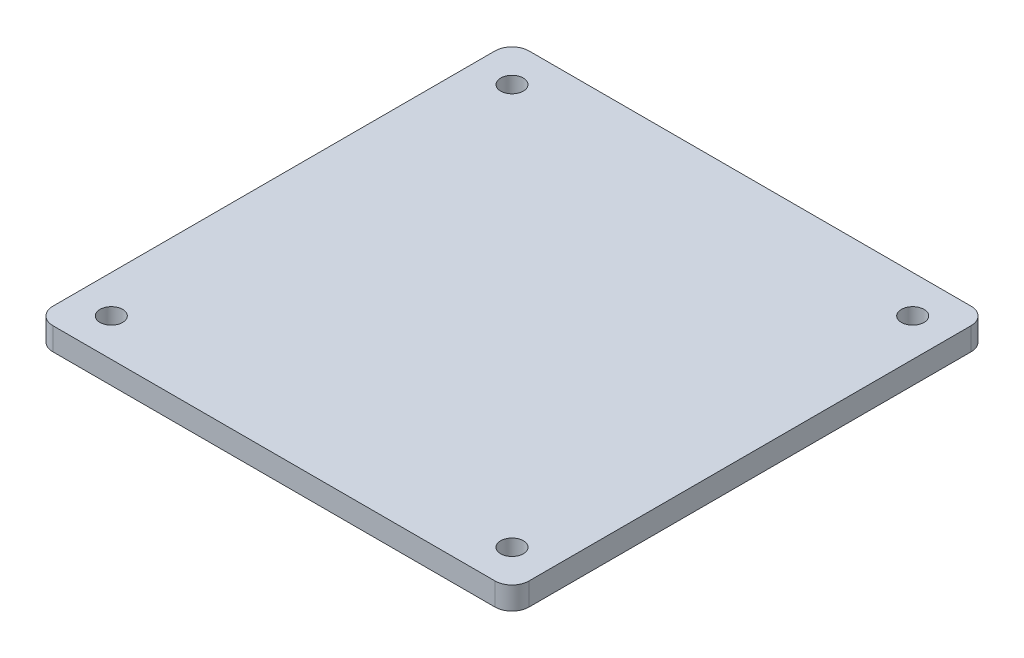
SolidWorks part; units mm, degrees
material "Plain Carbon Steel"
ref_plane "Front Plane" through (0, 0, 0) normal (0, 0, 1) x (1, 0, 0)
ref_plane "Top Plane" through (0, 0, 0) normal (0, 1, 0) x (1, 0, 0)
ref_plane "Right Plane" through (0, 0, 0) normal (1, 0, 0) x (0, 0, -1)
sketch "Sketch1" plane through (0, 0, 0) normal (0, 1, 0) x (1, 0, 0)
  line L0 (0, 0) -> (210, 0) construction
  line L1 (-195, -210) -> (195, -210)
  line L2 (-210, -195) -> (-210, 195)
  line L3 (-195, 210) -> (195, 210)
  line L4 (210, -195) -> (210, 195)
  line L5 (-210, -210) -> (210, 210) construction
  line L6 (-210, 210) -> (210, -210) construction
  line L7 (0, 0) -> (0, 11.2476) construction
  line L8 (0, 0) -> (0, 210) construction
  circle A0 centre (176.7767, 176.7767) radius 10
  arc A1 (195, -210) -> (210, -195) centre (195, -195) ccw
  arc A2 (-195, -210) -> (-210, -195) centre (-195, -195) cw
  arc A3 (-210, 195) -> (-195, 210) centre (-195, 195) cw
  arc A4 (195, 210) -> (210, 195) centre (195, 195) cw
  circle A5 centre (176.7767, -176.7767) radius 10
  circle A6 centre (-176.7767, -176.7767) radius 10
  circle A7 centre (-176.7767, 176.7767) radius 10
  point P0 (0, 0)
  dimension "D3" = 20
  dimension "D5" = 15
  dimension "D1" = 420
  dimension "D2" = 420
  dimension "D4" = 250
extrude "Boss-Extrude1" add sketch "Sketch1" along normal blind 20
